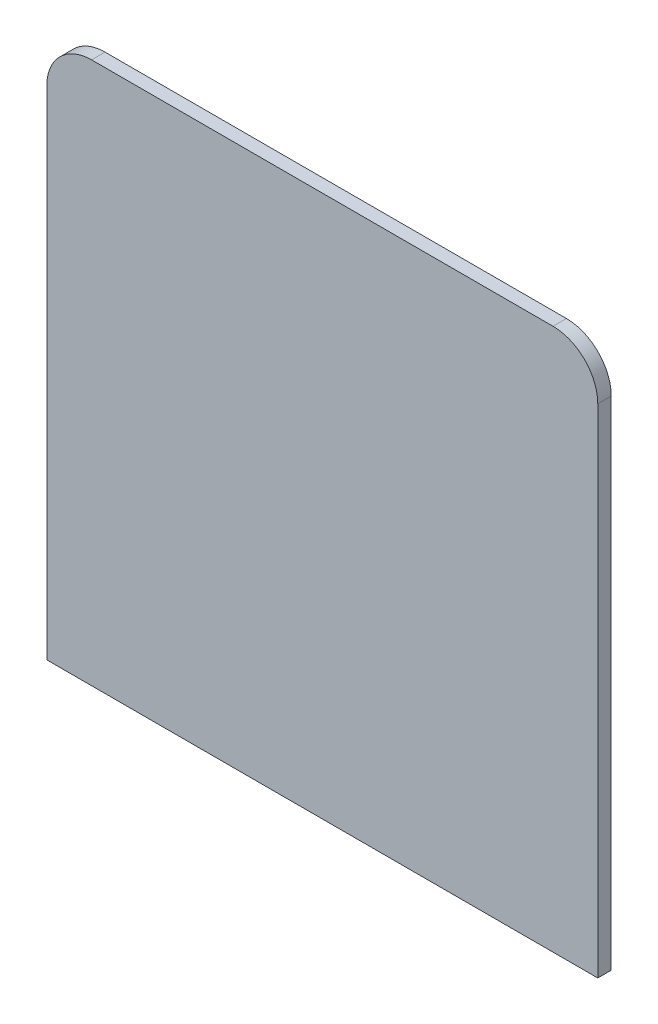
SolidWorks part; units mm, degrees
ref_plane "Front Plane" through (0, 0, 0) normal (0, 0, 1) x (1, 0, 0)
ref_plane "Top Plane" through (0, 0, 0) normal (0, 1, 0) x (1, 0, 0)
ref_plane "Right Plane" through (0, 0, 0) normal (1, 0, 0) x (0, 0, -1)
sketch "Sketch1" plane through (0, 0, 0) normal (0, 0, 1) x (1, 0, 0)
  line L1 (61.5, 60.5) -> (-61.5, 60.5)
  line L2 (61.5, 60.5) -> (61.5, -60.5)
  line L3 (61.5, -60.5) -> (-61.5, -60.5)
  line L4 (-61.5, 60.5) -> (-61.5, -60.5)
  line L5 (61.5, 60.5) -> (-61.5, -60.5) construction
  line L6 (61.5, -60.5) -> (-61.5, 60.5) construction
  point P0 (0, 0)
  dimension "D1" = 123
  dimension "D2" = 121
extrude "Boss-Extrude1" add sketch "Sketch1" along normal blind 3
fillet "Fillet1" radius 10 2 edges at (61.5, 60.5, 1.5) (-61.5, 60.5, 1.5)
